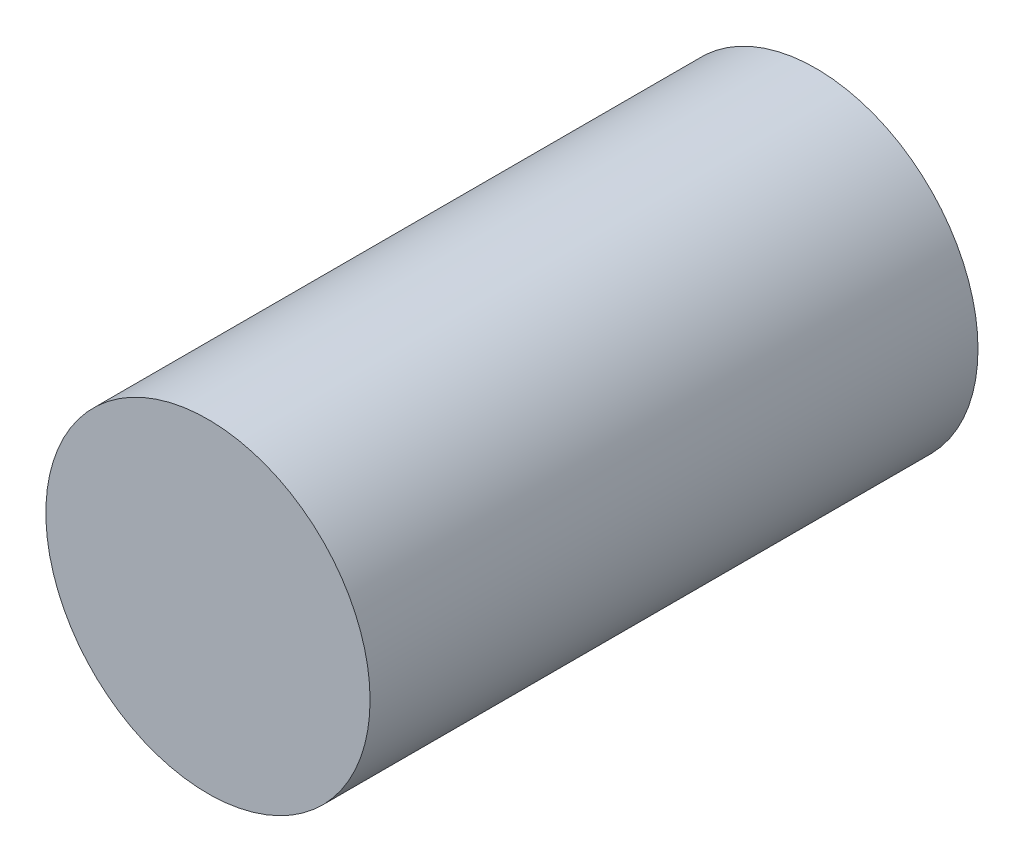
SolidWorks part; units mm, degrees
ref_plane "Front Plane" through (0, 0, 0) normal (0, 0, 1) x (1, 0, 0)
ref_plane "Top Plane" through (0, 0, 0) normal (0, 1, 0) x (1, 0, 0)
ref_plane "Right Plane" through (0, 0, 0) normal (1, 0, 0) x (0, 0, -1)
sketch "Sketch1" plane through (0, 0, 0) normal (0, 0, 1) x (1, 0, 0)
  circle A0 centre (0, 0) radius 20
extrude "Boss-Extrude1" add sketch "Sketch1" along normal blind 75
